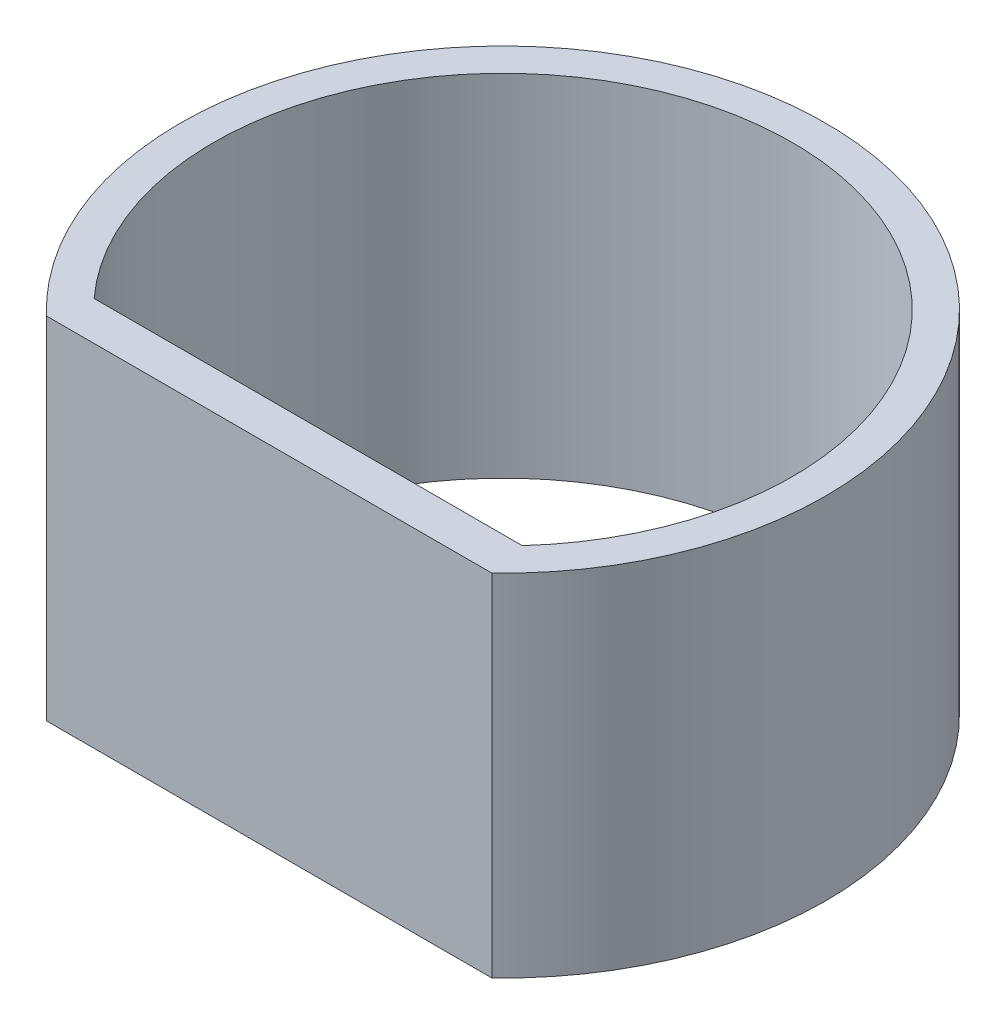
SolidWorks part; units mm, degrees
ref_plane "Front Plane" through (0, 0, 0) normal (0, 0, 1) x (1, 0, 0)
ref_plane "Top Plane" through (0, 0, 0) normal (0, 1, 0) x (1, 0, 0)
ref_plane "Right Plane" through (0, 0, 0) normal (1, 0, 0) x (0, 0, -1)
sketch "Sketch2" plane through (0, 0, 0) normal (0, 1, 0) x (1, 0, 0)
  line L0 (4, -4.2) -> (-4, -4.2)
  line L1 (-3.8458, -3.5) -> (3.8458, -3.5)
  arc A1 (-4, -4.2) -> (4, -4.2) centre (0, 0) cw
  arc A2 (-3.8458, -3.5) -> (3.8458, -3.5) centre (0, 0) cw
  dimension "D1" = 5.2
  dimension "D4" = 5.8
  dimension "D2" = 8
  dimension "D3" = 3.5
extrude "Boss-Extrude1" add sketch "Sketch2" along normal blind 6.3
